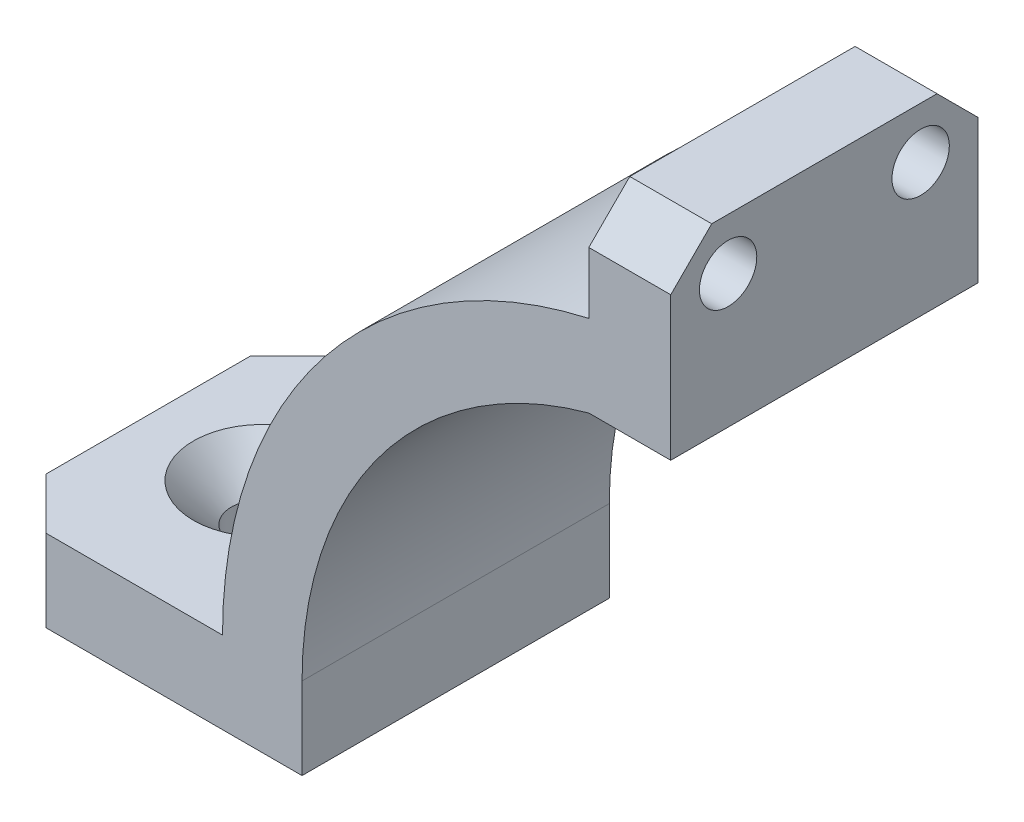
SolidWorks part; units mm, degrees
ref_plane "Front Plane" through (0, 0, 0) normal (0, 0, 1) x (1, 0, 0)
ref_plane "Top Plane" through (0, 0, 0) normal (0, 1, 0) x (1, 0, 0)
ref_plane "Right Plane" through (0, 0, 0) normal (1, 0, 0) x (0, 0, -1)
sketch "Sketch1" plane through (0, 0, 0) normal (0, 0, 1) x (1, 0, 0)
  line L0 (0, 0) -> (0, 50000) construction
  line L2 (-19, 0) -> (-19, -4)
  line L3 (-19, -4) -> (-34, -4)
  line L4 (-34, -4) -> (-34, 0)
  line L5 (-34, 0) -> (-22.8832, 0)
  line L6 (-5, 22.3303) -> (-5, 27.3303)
  line L7 (-5, 27.3303) -> (-1, 27.3303)
  line L8 (-1, 27.3303) -> (-1, 18.3303)
  line L9 (-1, 18.3303) -> (-5, 18.3303)
  arc A0 (-19, 0) -> (-5, 18.3303) centre (0, 0) cw
  arc A1 (-22.8832, 0) -> (-5, 22.3303) centre (0, 0) cw
  dimension "D2" = 19
  dimension "D1" = 4
  dimension "D3" = 15
  dimension "D4" = 4
  dimension "D5" = 4
  dimension "D6" = 9
  dimension "D7" = 1
extrude "Boss-Extrude1" add sketch "Sketch1" along normal blind 15
chamfer "Chamfer1" distance 2.5 2 edges at (-34, -2, 0) (-34, -2, 15)
sketch "Sketch2" plane through (-5, 0, 0) normal (-1, 0, 0) x (0, 0, 1)
  line L0 (15, 27.3303) -> (15, 22.3303) construction
  line L1 (0, 27.3303) -> (0, 22.3303) construction
  circle A0 centre (2.8, 24.8303) radius 1.4
  circle A1 centre (12.2, 24.8303) radius 1.4
  point P8 (0, 24.8303)
  dimension "D1" = 2.8
  dimension "D2" = 2.8
  dimension "D3" = 2.8
extrude "Cut-Extrude1" cut sketch "Sketch2" against normal blind 15
chamfer "Chamfer2" distance 2 angle 45 2 edges at (-3, 27.3303, 15) (-3, 27.3303, 0)
sketch "Sketch3" plane through (0, 0, 0) normal (0, 1, 0) x (1, 0, 0)
  line L0 (-34, -12.5) -> (-34, -2.5) construction
  line L2 (-22.8832, 0) -> (-34, 0.1) construction
  line L3 (45.4373, 0.1) -> (-44.4791, 0.1) construction
  circle A0 centre (-28.4416, -7.5) radius 1.4
  point P2 (-28.4416, 0.05)
  point P5 (-34, -7.5)
  dimension "D1" = 2.8
extrude "Cut-Extrude2" cut sketch "Sketch3" against normal through all contours A0
hole_wizard "CSK for M3 SFHCS1" positions "3DSketch1" profile "Sketch4" countersink size "M3" standard "ANSI Metric"
sketch3d "3DSketch1"
  line L0 (-28.4416, -4, 7.5) -> (-28.4416, 0, 7.5) construction
  point P0 (-28.4416, 0, 7.5)
  point P3 (-28.4504, 0, 7.2456)
  point P7 (-28.4416, 0, 7.5)
sketch "Sketch4" plane through (-28.4416, 0, 7.5) normal (1, 0, 0) x (0, 0, 1)
  line L0 (0, 0) -> (0, 32)
  line L1 (0, 32) -> (1.5, 31.0987)
  line L2 (1.5, 31.0987) -> (1.5, 1.86)
  line L3 (1.5, 1.86) -> (3.36, 0)
  line L5 (3.36, 0) -> (0, 0)
  line L6 (-1.5, 1.86) -> (-3.36, 0) construction
  line L10 (0, 32) -> (-1.5, 31.0987) construction
  line L11 (0, -6.35) -> (0, 107.95) construction
  dimension "Hole Dia." = 3
  dimension "Hole Depth" = 32
  dimension "Near C'Sink Dia." = 6.72
  dimension "Near C'Sink Angle" = 90
  dimension "Drill Angle" = 118
